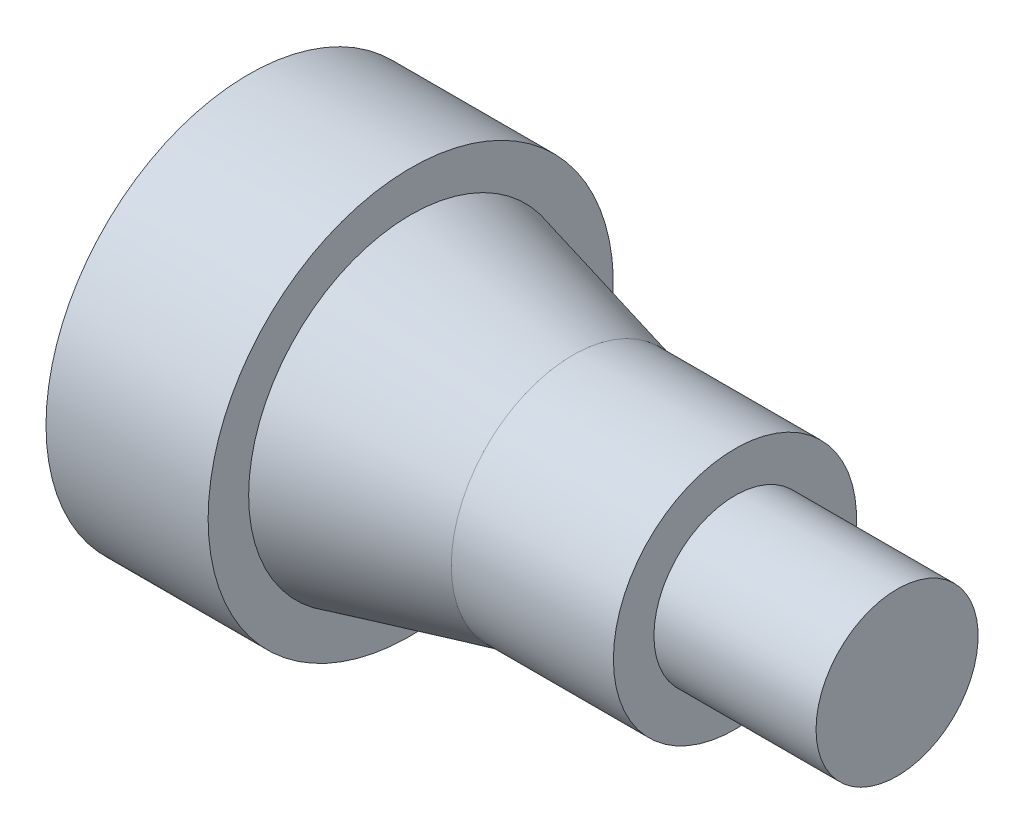
SolidWorks part; units mm, degrees
ref_plane "정면" through (0, 0, 0) normal (0, 0, 1) x (1, 0, 0)
ref_plane "윗면" through (0, 0, 0) normal (0, 1, 0) x (1, 0, 0)
ref_plane "우측면" through (0, 0, 0) normal (1, 0, 0) x (0, 0, -1)
sketch "스케치1" plane through (0, 0, 0) normal (0, 1, 0) x (1, 0, 0)
  line L0 (-49.7589, 0) -> (104.4936, 0) construction
  line L1 (-40, 0) -> (-40, 25)
  line L2 (-40, 25) -> (-20, 25)
  line L3 (-20, 25) -> (-20, 20)
  line L4 (-20, 20) -> (0, 15)
  line L5 (0, 15) -> (20, 15)
  line L6 (20, 15) -> (20, 10)
  line L7 (20, 10) -> (40, 10)
  line L8 (40, 10) -> (40, 0)
  line L9 (-40, 0) -> (40, 0)
  point P12 (0, 0)
  dimension "D1" = 50
  dimension "D2" = 20
  dimension "D3" = 30
  dimension "D4" = 15
  dimension "D5" = 20
  dimension "D6" = 20
  dimension "D7" = 20
  dimension "D8" = 20
  dimension "D9" = 40
revolve "회전1" add sketch "스케치1" angle 360 about L0
